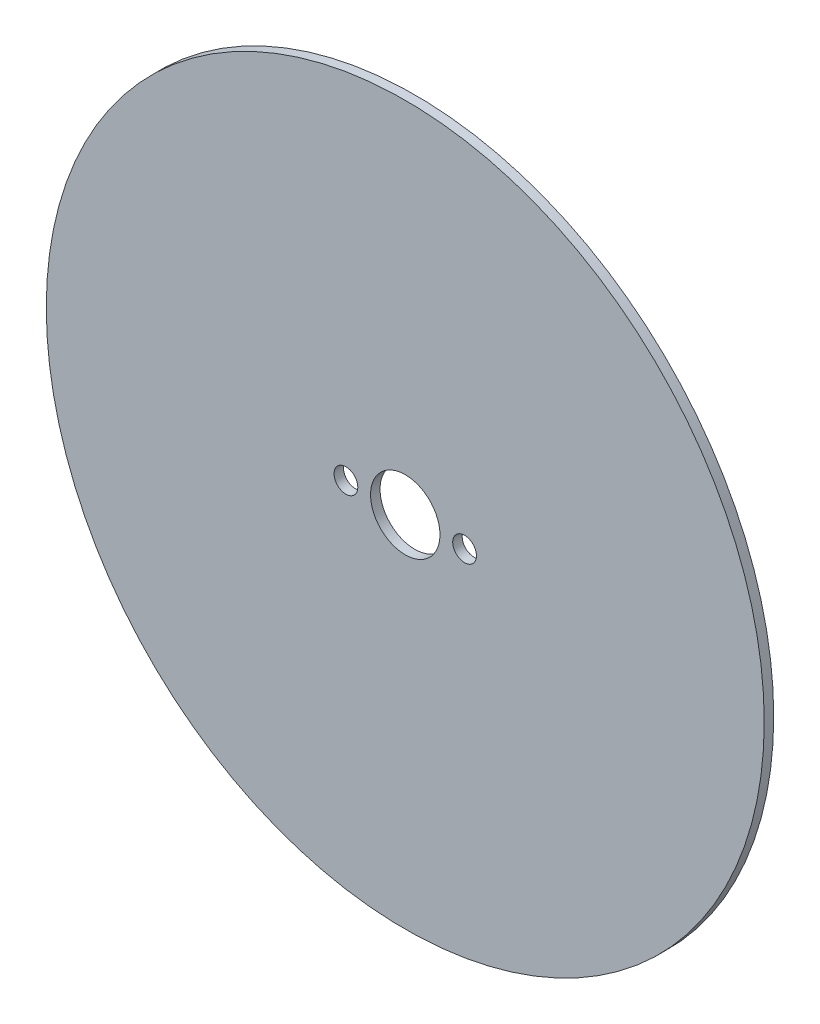
SolidWorks part; units mm, degrees
ref_plane "Plan de face" through (0, 0, 0) normal (0, 0, 1) x (1, 0, 0)
ref_plane "Plan de dessus" through (0, 0, 0) normal (0, 1, 0) x (1, 0, 0)
ref_plane "Plan de droite" through (0, 0, 0) normal (1, 0, 0) x (0, 0, -1)
sketch "Esquisse1" plane through (0, 0, 0) normal (0, 0, 1) x (1, 0, 0)
  line L0 (-5, 0) -> (5, 0) construction
  circle A0 centre (0, 0) radius 30.2539
  circle A2 centre (5, 0) radius 1
  circle A3 centre (0, 0) radius 2.925
  circle A4 centre (-5, 0) radius 1
  point P12 (0, 0)
  dimension "D1" = 60.5078
  dimension "D2" = 10
  dimension "D3" = 5.85
  dimension "D4" = 2
extrude "Boss.-Extru.1" add sketch "Esquisse1" against normal blind 0.8 contours A0 A3
other "Indent2" [suppressed] parameters "D1"=10, "D2"=0
